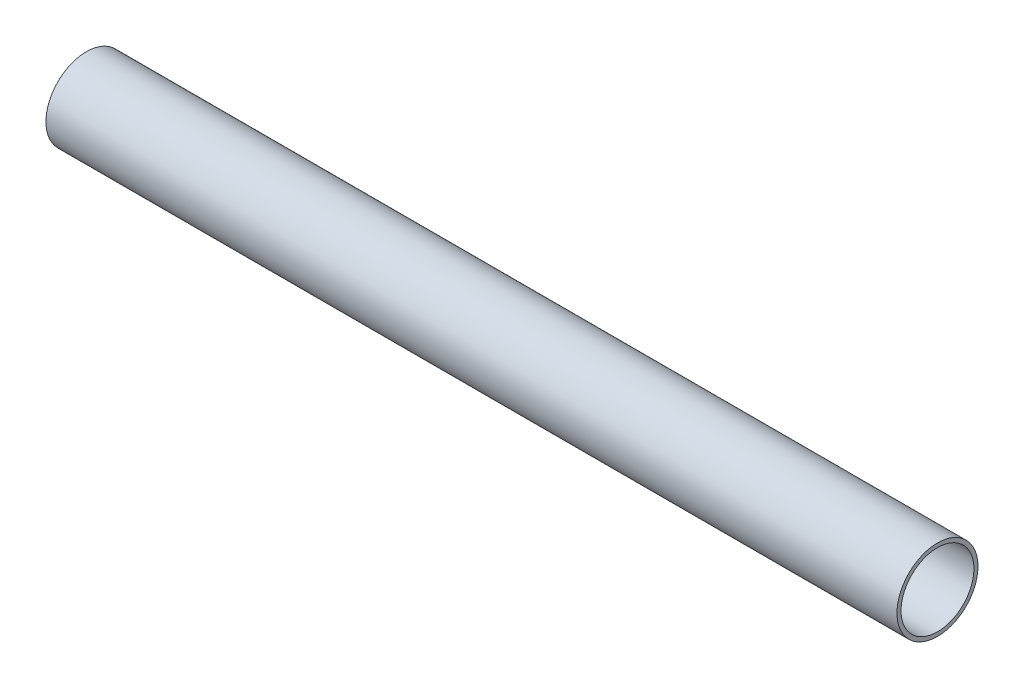
SolidWorks part; units mm, degrees
material "PC High Viscosity"
ref_plane "Front Plane" through (0, 0, 0) normal (0, 0, 1) x (1, 0, 0)
ref_plane "Top Plane" through (0, 0, 0) normal (0, 1, 0) x (1, 0, 0)
ref_plane "Right Plane" through (0, 0, 0) normal (1, 0, 0) x (0, 0, -1)
sketch "Sketch1" plane through (0, 0, 0) normal (1, 0, 0) x (0, 0, -1)
  circle A0 centre (0, 0) radius 15.875
  dimension "D1" = 31.75
extrude "Extrude-Thin1" add sketch "Sketch1" along normal mid plane 333.375 thin thin type one direction reverse wall 1.5875
sketch "Sketch2" plane through (0, 0, 0) normal (0, 0, 1) x (1, 0, 0)
  line L0 (-166.6875, -15.875) -> (166.6875, -15.875) construction
  line L1 (104.4125, -15.875) -> (125.4125, -15.875)
  line L2 (104.4125, -15.875) -> (104.4125, 15.875)
  line L3 (104.4125, 15.875) -> (125.4125, 15.875)
  line L4 (125.4125, -15.875) -> (125.4125, 15.875)
  line L5 (166.6875, 15.875) -> (-166.6875, 15.875) construction
  line L6 (166.6875, -15.875) -> (166.6875, 15.875) construction
  line L7 (0, 0) -> (0, 11.1276) construction
  line L8 (-125.4125, -15.875) -> (-125.4125, 15.875)
  line L9 (-104.4125, 15.875) -> (-125.4125, 15.875)
  line L10 (-104.4125, -15.875) -> (-104.4125, 15.875)
  line L11 (-104.4125, -15.875) -> (-125.4125, -15.875)
  line L13 (166.6875, -15.875) -> (164.3634, -15.875)
  line L14 (166.6875, -15.875) -> (166.6875, 15.875)
  line L15 (166.6875, 15.875) -> (164.3634, 15.875)
  line L16 (164.3634, -15.875) -> (164.3634, 15.875)
  dimension "D1" = 41.275
  dimension "D2" = 21
  dimension "D3" = 2.3241
equation "\"D2@Sketch2\"=21mm"
